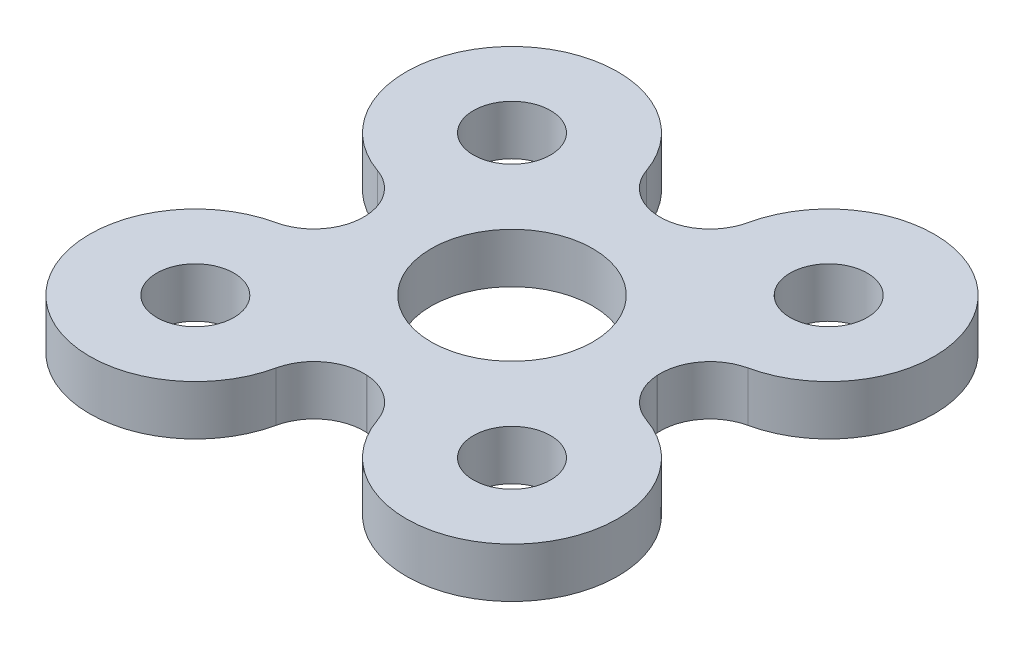
SolidWorks part; units mm, degrees
material "Thermoplastic p (TPO), Lucobit"
ref_plane "Front Plane" through (0, 0, 0) normal (0, 0, 1) x (1, 0, 0)
ref_plane "Top Plane" through (0, 0, 0) normal (0, 1, 0) x (1, 0, 0)
ref_plane "Right Plane" through (0, 0, 0) normal (1, 0, 0) x (0, 0, -1)
sketch "Sketch1" plane through (0, 0, 0) normal (0, 1, 0) x (1, 0, 0)
  line L0 (-9.0001, 0) -> (9.0001, 0) construction
  line L1 (0, 0) -> (6.3641, 6.3641) construction
  line L2 (-5.6569, 5.6569) -> (0, 0) construction
  line L3 (-6.3641, -6.3641) -> (0, 0) construction
  line L4 (0, 0) -> (5.6569, -5.6569) construction
  circle A0 centre (0, 0) radius 9.0001 construction
  circle A1 centre (0, 0) radius 8 construction
  circle A2 centre (-6.3641, -6.3641) radius 1.55
  circle A3 centre (6.3641, 6.3641) radius 1.55
  circle A4 centre (5.6569, -5.6569) radius 1.55
  circle A5 centre (-5.6569, 5.6569) radius 1.55
  circle A6 centre (0, 0) radius 3.25
  arc A7 (-1.4391, 6.1793) -> (-6.1857, 1.4399) centre (-5.6569, 5.6569) ccw
  arc A8 (-6.1857, -2.1178) -> (-2.1181, -6.1793) centre (-6.3641, -6.3641) ccw
  arc A9 (1.4391, -6.1793) -> (6.1857, -1.4399) centre (5.6569, -5.6569) ccw
  arc A10 (6.1857, 2.1178) -> (2.1181, 6.1793) centre (6.3641, 6.3641) ccw
  arc A12 (-6.1857, 1.4399) -> (-6.1857, -2.1178) centre (-9.2, -0.339) cw
  arc A13 (-1.4391, 6.1793) -> (2.1181, 6.1793) centre (0.3395, 9.1937) ccw
  arc A14 (6.1857, 2.1178) -> (6.1857, -1.4399) centre (9.2, 0.339) ccw
  arc A15 (1.4391, -6.1793) -> (-2.1181, -6.1793) centre (-0.3395, -9.1937) ccw
  dimension "D1" = 18.0003
  dimension "D2" = 16
  dimension "D3" = 3.1
  dimension "D8" = 6.5
  dimension "D9" = 8.5
  dimension "D10" = 3.5
  dimension "D11" = 9.2
  dimension "D12" = 9.2
  dimension "D13" = 9.2
  dimension "D14" = 9.2
  dimension "D4" = 45
  dimension "D5" = 45
  dimension "D6" = 45
  dimension "D7" = 45
extrude "Boss-Extrude2" add sketch "Sketch1" against normal blind 2
fillet "Fillet1" radius 2 8 edges at (2.1181, -1, -6.1793) (-1.4391, -1, -6.1793) (6.1857, -1, 1.4399) (6.1857, -1, -2.1178) (1.4391, -1, 6.1793) (-2.1181, -1, 6.1793) (-6.1857, -1, 2.1178) (-6.1857, -1, -1.4399)
